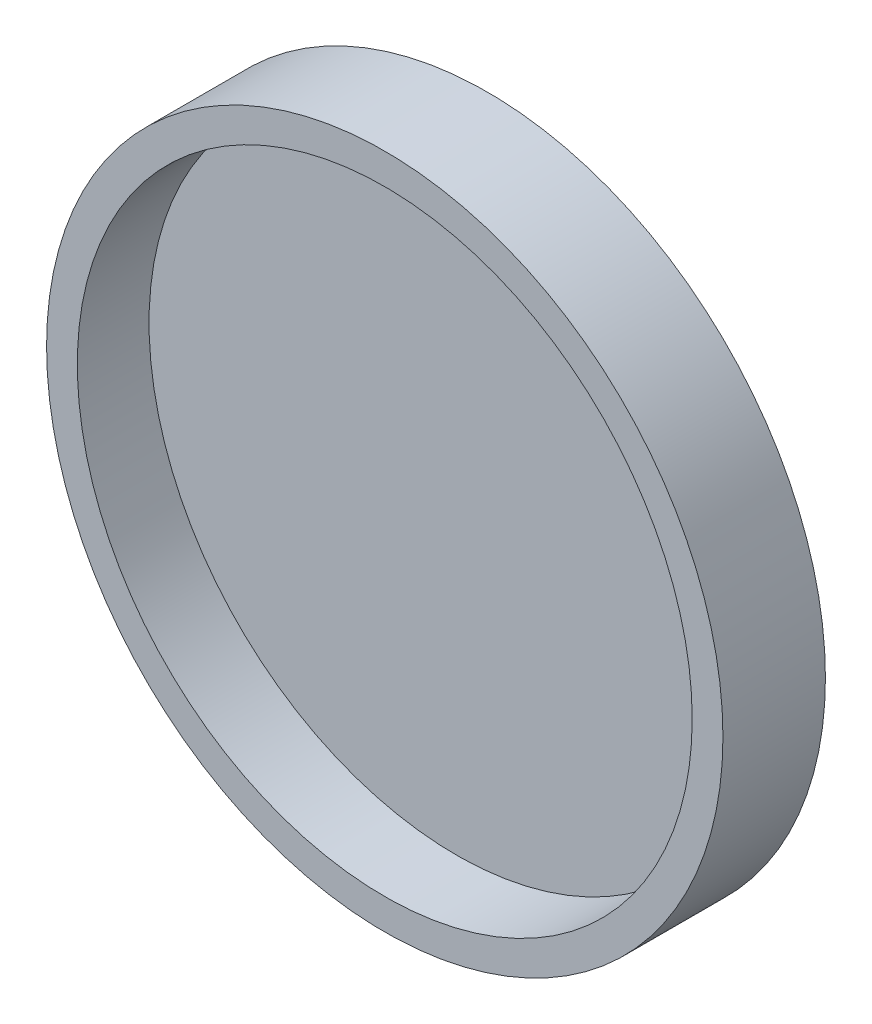
SolidWorks part; units mm, degrees
ref_plane "Front" through (0, 0, 0) normal (0, 0, 1) x (1, 0, 0)
ref_plane "Top" through (0, 0, 0) normal (0, 1, 0) x (1, 0, 0)
ref_plane "Right" through (0, 0, 0) normal (1, 0, 0) x (0, 0, -1)
other "Configuration Table"
sketch "Sketch1" plane through (0, 0, 0) normal (0, 0, 1) x (1, 0, 0)
  circle A0 centre (0, 0) radius 33
  dimension "D1" = 66
extrude "Boss-Extrude1" add sketch "Sketch1" along normal blind 10
shell "Shell1" thickness 3
